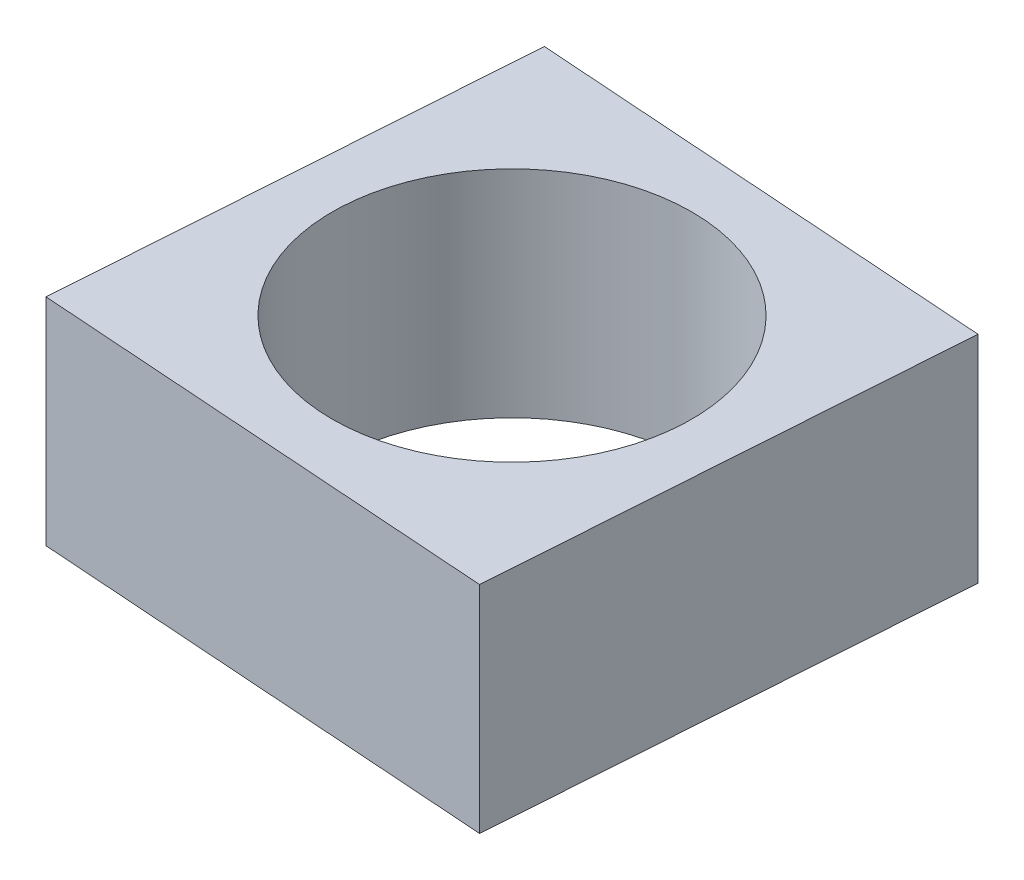
SolidWorks part; units mm, degrees
ref_plane "Front Plane" through (0, 0, 0) normal (0, 0, 1) x (1, 0, 0)
ref_plane "Top Plane" through (0, 0, 0) normal (0, 1, 0) x (1, 0, 0)
ref_plane "Right Plane" through (0, 0, 0) normal (1, 0, 0) x (0, 0, -1)
sketch "Sketch2" plane through (0, 0, 0) normal (0, 1, 0) x (1, 0, 0)
  line L0 (0, 0) -> (0.4508, 6.4844)
  line L1 (0.4508, 6.4844) -> (-6.0336, 6.9351)
  line L2 (-6.0336, 6.9351) -> (-6.4844, 0.4508)
  line L3 (-6.4844, 0.4508) -> (0, 0)
extrude "Boss-Extrude1" add sketch "Sketch2" along normal blind 3
sketch "Sketch3" plane through (0, 3, 0) normal (0, 1, 0) x (1, 0, 0)
  circle A0 centre (-3.0168, 3.4676) radius 2.5
extrude "Cut-Extrude1" cut sketch "Sketch3" against normal blind 3
